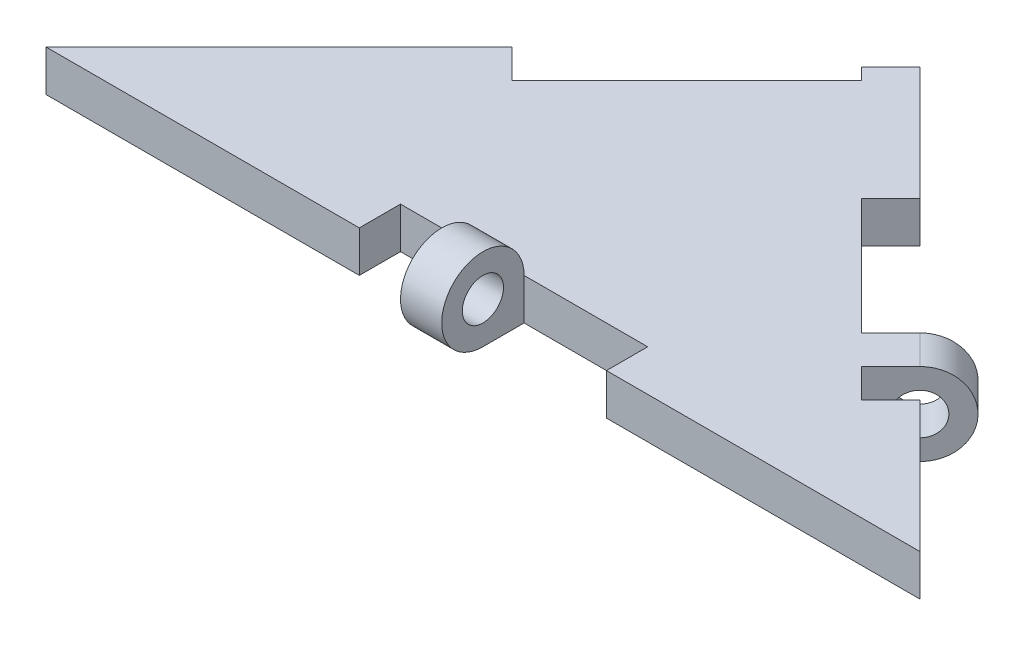
SolidWorks part; units mm, degrees
material "PET"
ref_plane "Front Plane" through (0, 0, 0) normal (0, 0, 1) x (1, 0, 0)
ref_plane "Top Plane" through (0, 0, 0) normal (0, 1, 0) x (1, 0, 0)
ref_plane "Right Plane" through (0, 0, 0) normal (1, 0, 0) x (0, 0, -1)
other "Center of Mass"
sketch "Sketch1" plane through (0, 0, 0) normal (0, 1, 0) x (1, 0, 0)
  line L0 (-53.033, 0) -> (53.033, 0)
  line L1 (-53.033, 0) -> (0, 53.033)
  line L2 (0, 53.033) -> (53.033, 0)
  dimension "D1" = 75
extrude "Boss-Extrude1" add sketch "Sketch1" along normal blind 5
sketch "Sketch2" plane through (0, 5, 0) normal (0, 1, 0) x (1, 0, 0)
  line L0 (-15, 0) -> (15, 0)
  line L1 (-15, 0) -> (-15, 5)
  line L2 (15, 0) -> (15, 5)
  line L3 (-15, 5) -> (15, 5)
  line L4 (-53.033, 0) -> (53.033, 0) construction
  line L5 (0, 0) -> (0, 8.7982) construction
  line L6 (-3.5355, 49.4975) -> (-24.7487, 28.2843)
  line L7 (-3.5355, 49.4975) -> (0, 45.9619)
  line L8 (-24.7487, 28.2843) -> (-21.2132, 24.7487)
  line L9 (0, 45.9619) -> (-21.2132, 24.7487)
  line L10 (0, 53.033) -> (-53.033, 0) construction
  line L11 (53.033, 0) -> (0, 53.033) construction
  dimension "D1" = 5
  dimension "D2" = 30
  dimension "D3" = 5
  dimension "D4" = 30
  dimension "D5" = 35
extrude "Cut-Extrude1" cut sketch "Sketch2" against normal blind 5
sketch "Sketch3" plane through (0, 0, 0) normal (0, -1, 0) x (1, 0, 0)
  line L0 (15.9099, -37.1231) -> (37.1231, -15.9099)
  line L1 (15.9099, -37.1231) -> (12.3744, -33.5876)
  line L2 (37.1231, -15.9099) -> (33.5876, -12.3744)
  line L3 (12.3744, -33.5876) -> (33.5876, -12.3744)
  line L4 (53.033, 0) -> (0, -53.033) construction
  line L5 (26.5165, -26.5165) -> (19.6082, -19.6082) construction
  dimension "D1" = 5
  dimension "D2" = 30
extrude "Cut-Extrude2" cut sketch "Sketch3" against normal blind 5
sketch "Sketch5" plane through (15, 0, 0) normal (-1, 0, 0) x (0, 0, 1)
  circle A0 centre (0, 5) radius 5
  circle A1 centre (0, 5) radius 2.5
  dimension "D1" = 5
extrude "Boss-Extrude2" add sketch "Sketch5" along normal blind 5 from offset 15
sketch "Sketch6" plane through (10.6066, 0, 10.6066) normal (-0.7071, 0, -0.7071) x (-0.7071, 0, 0.7071)
  circle A0 centre (-37.5, 0) radius 5
  circle A1 centre (-37.5, 0) radius 2.5
  dimension "D1" = 5
extrude "Boss-Extrude3" add sketch "Sketch6" along normal blind 5 from offset 5
sketch "Sketch7" plane through (0, 0, 0) normal (0, -1, 0) x (1, 0, 0)
  line L0 (-21.1541, -31.8789) -> (0, -53.033)
  line L1 (-21.1541, -31.8789) -> (-19.0328, -29.7576)
  line L2 (0, -53.033) -> (2.1213, -50.9117)
  line L3 (-19.0328, -29.7576) -> (2.1213, -50.9117)
  dimension "D1" = 3
extrude "Cut-Extrude3" cut sketch "Sketch7" against normal blind 10
chamfer "Chamfer1" [suppressed] distance 2 angle 45
other "Center of Mass Reference Point1"
